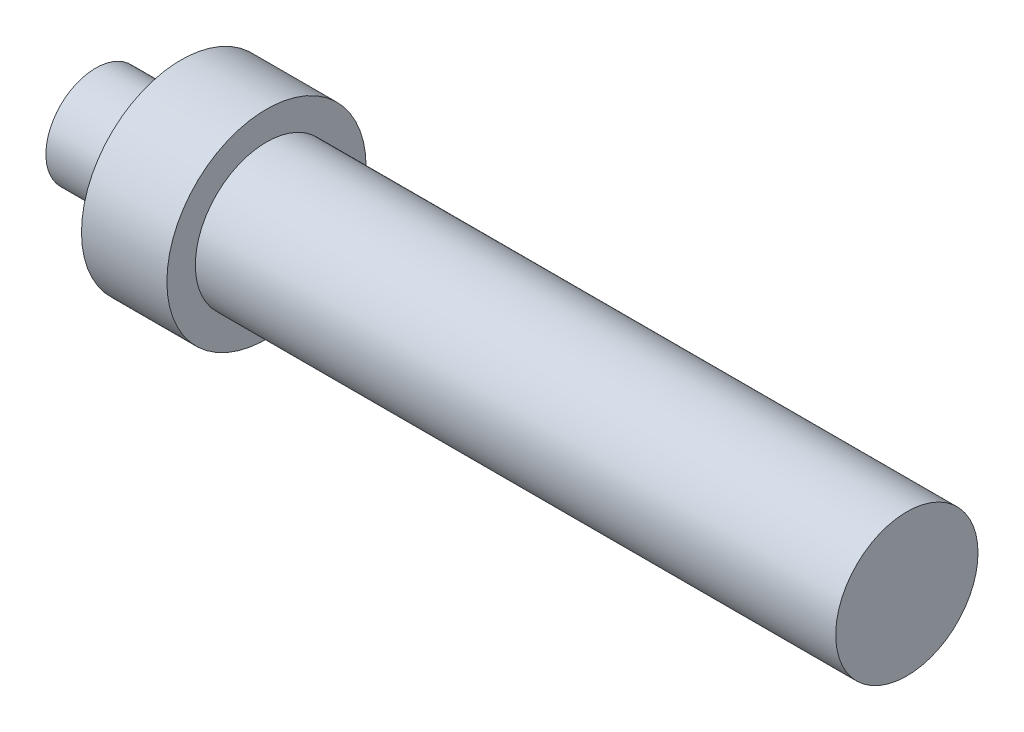
SolidWorks part; units mm, degrees
ref_plane "Front Plane" through (0, 0, 0) normal (0, 0, 1) x (1, 0, 0)
ref_plane "Top Plane" through (0, 0, 0) normal (0, 1, 0) x (1, 0, 0)
ref_plane "Right Plane" through (0, 0, 0) normal (1, 0, 0) x (0, 0, -1)
sketch "Sketch1" plane through (0, 0, 0) normal (0, 0, 1) x (1, 0, 0)
  line L0 (0, 0) -> (0, 3.5)
  line L1 (0, 3.5) -> (6, 3.5)
  line L2 (6, 3.5) -> (6, 7)
  line L3 (6, 7) -> (12, 7)
  line L4 (12, 7) -> (12, 5)
  line L5 (12, 5) -> (57, 5)
  line L6 (57, 5) -> (57, 0)
  line L7 (57, 0) -> (0, 0)
  point P3 (18.4104, 0)
  dimension "D1" = 3.5
  dimension "D2" = 6
  dimension "D3" = 6
  dimension "D4" = 7
  dimension "D5" = 45
  dimension "D6" = 5
revolve "Revolve1" add sketch "Sketch1" angle 360 about L7
